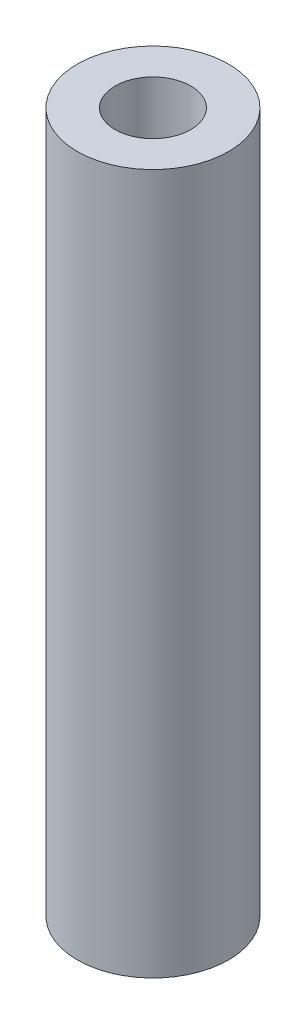
SolidWorks part; units mm, degrees
ref_plane "Front Plane" through (0, 0, 0) normal (0, 0, 1) x (1, 0, 0)
ref_plane "Top Plane" through (0, 0, 0) normal (0, 1, 0) x (1, 0, 0)
ref_plane "Right Plane" through (0, 0, 0) normal (1, 0, 0) x (0, 0, -1)
sketch "Sketch1" plane through (0, 0, 0) normal (0, 1, 0) x (1, 0, 0)
  circle A0 centre (0, 0) radius 2
  circle A1 centre (0, 0) radius 4
  dimension "D1" = 4
  dimension "D2" = 8
extrude "Boss-Extrude1" add sketch "Sketch1" along normal blind 37
